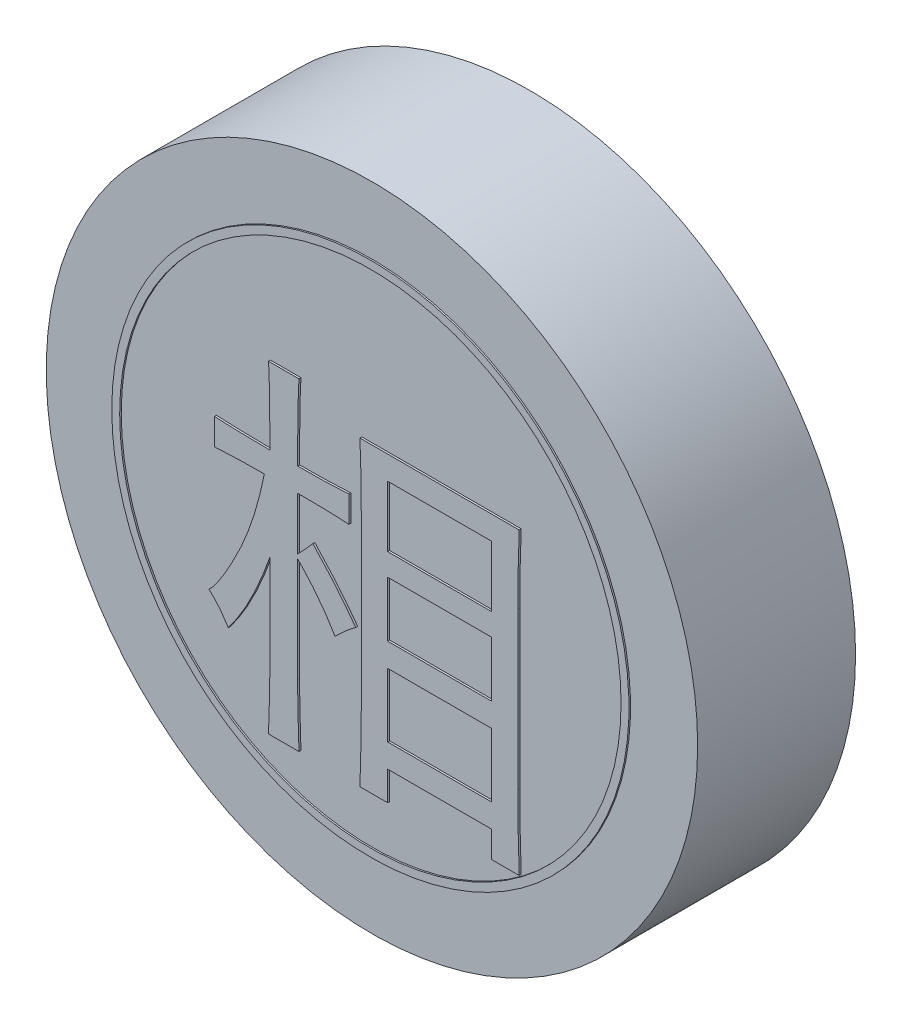
SolidWorks part; units mm, degrees
ref_plane "前视基准面" through (0, 0, 0) normal (0, 0, 1) x (1, 0, 0)
ref_plane "上视基准面" through (0, 0, 0) normal (0, 1, 0) x (1, 0, 0)
ref_plane "右视基准面" through (0, 0, 0) normal (1, 0, 0) x (0, 0, -1)
other "Configuration Table"
sketch "草图1" plane through (0, 0, 0) normal (0, 0, 1) x (1, 0, 0)
  circle A0 centre (0, 0) radius 16.5
  dimension "D1" = 33
extrude "Diameter33_Height8" add sketch "草图1" against normal blind 8
sketch "草图2" plane through (0, 0, 0) normal (0, 0, 1) x (1, 0, 0)
  text T0 "相" font "SimHei" height 12
extrude "Character_相" add sketch "草图2" along normal blind 0.1
sketch "草图3" plane through (0, 0, 0) normal (0, 0, 1) x (1, 0, 0)
  circle A0 centre (0, 0) radius 13.1
  circle A1 centre (0, 0) radius 12.7
extrude "Ink_ring" add sketch "草图3" along normal blind 0.08
